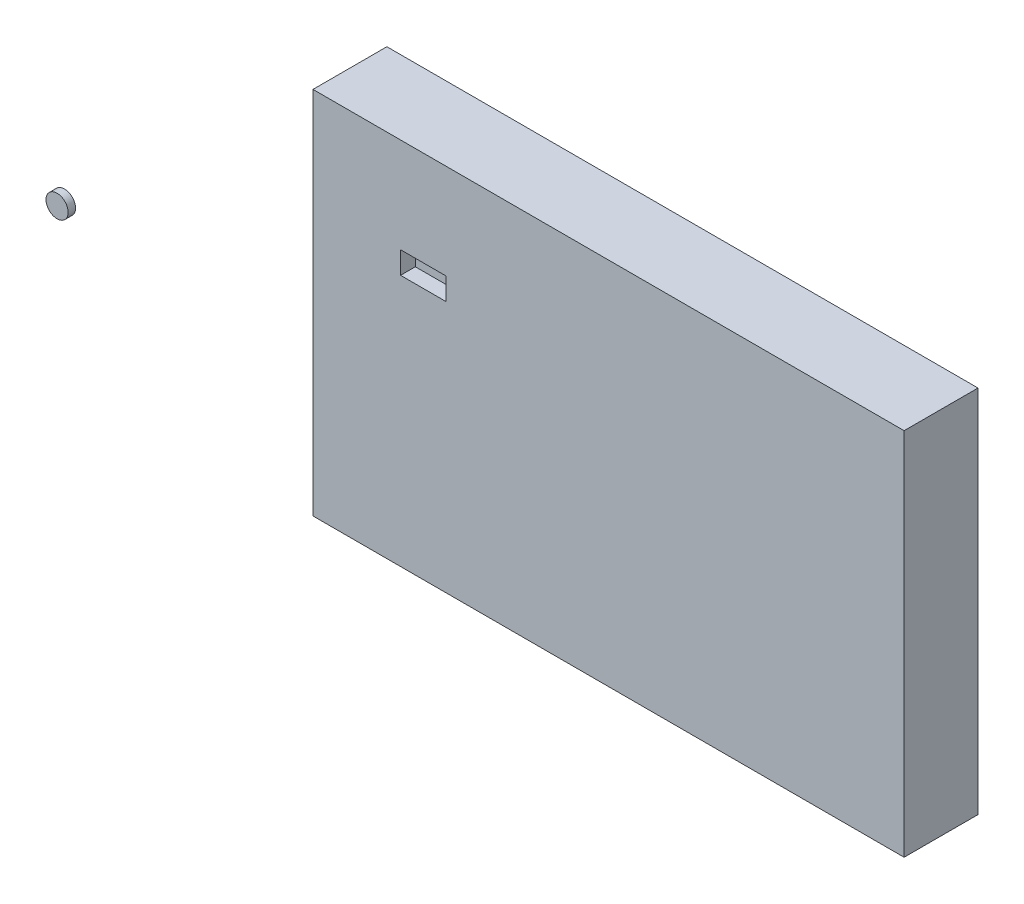
SolidWorks part; units mm, degrees
material "AISI 1020"
ref_plane "Front" through (0, 0, 0) normal (0, 0, 1) x (1, 0, 0)
ref_plane "Top" through (0, 0, 0) normal (0, 1, 0) x (1, 0, 0)
ref_plane "Right" through (0, 0, 0) normal (1, 0, 0) x (0, 0, -1)
sketch "Sketch1" plane through (0, 0, 0) normal (0, 0, 1) x (1, 0, 0)
  line L1 (0, 0) -> (80, 0)
  line L2 (0, 0) -> (0, 50)
  line L3 (0, 50) -> (80, 50)
  line L4 (80, 0) -> (80, 50)
  dimension "D1" = 80
  dimension "D2" = 50
extrude "Boss-Extrude1" add sketch "Sketch1" along normal blind 10
sketch "Sketch2" plane through (0, 0, 10) normal (0, 0, 1) x (1, 0, 0)
  line L1 (11.8518, 37.134) -> (18.0091, 37.134)
  line L2 (11.8518, 37.134) -> (11.8518, 34.134)
  line L3 (11.8518, 34.134) -> (18.0091, 34.134)
  line L4 (18.0091, 37.134) -> (18.0091, 34.134)
  dimension "D1" = 3
extrude "Cut-Extrude1" cut sketch "Sketch2" against normal blind 2
sketch "Sketch3" plane through (0, 0, 0) normal (0, 0, 1) x (1, 0, 0)
  circle A0 centre (-43.6336, 10.0141) radius 1.5
  dimension "D1" = 3
extrude "Boss-Extrude2" add sketch "Sketch3" along normal blind 1 separate body
equation "\"NumDocs\"= swApp.GetDocumentCount  'Automatic variable \"swApp\""
equation "\"UpdateStamp\"= Part.GetUpdateStamp 'Pre-loaded variable \"Part\""
equation "\"Val1\"= MsgBox(\"Currently active document: \" & swApp.ActiveDoc.GetTitle & vbCrLf & \"This message generated by: \" & Part.GetTitle) 'ActiveDoc and Part can be different"
equation "\"Val2\"= msgbox(Part.Extension.CustomPropertyManager(\"\").Get(\"MycustomProperty\"))  '\"Stringing together\" objects"
equation "\"Val3\"= 1:: Dim myStr as String:: If (Len(Part.GetMaterialPropertyName2(Part.ConfigurationManager.ActiveConfiguration.Name, myStr))<1) Then Part.Extension.RunCommand swCommands_EditMaterial,\"\" '\"::\" for multiple lines"
equation "\"Val5\"=part.extension.showsmartmessage(\"SmartMessages look like this!\",10000,true,true) 'A SmartMessage"
equation "\"Val6\"= Part.Extension.CustomPropertyManager(\"\").Set(\"DocLe\" & \"velProp\", \"Document level\") 'Setting a document-level property"
equation "\"Val7\"= Part.Extension.CustomPropertyManager(Part.ConfigurationManager.ActiveConfiguration.Name).Set(\"ConfigSpe\" & \"cProp\", \"Set for \" & Part.ConfigurationManager.ActiveConfiguration.Name & \" configuration\") 'Setting a config-specific property"
equation "\"Val9\"= Part.Extension.CustomPropertyManager(\"\").Set(\"NonExiste\" & \"ntProp\", \"This does not work\") 'Can't set a property that doesn't exist"
equation "\"Val10\"= Part.Extension.CustomPropertyManager(\"\").Delete(\"MightExi\" & \"stProp\") ::Part.Extension.CustomPropertyManager(\"\").Add2 \"MightExi\" & \"stProp\", swCustomInfoText, \"Guaranteed existence\" 'Use 2 lines to delete (if exists) then add"
equation "\"FileAgeInDays\"= Round(cDate(Part.SummaryInfo(swSumInfoSaveDate))-cDate(Part.SummaryInfo(swSumInfoCreateDate)),0) 'Manipulate file properties"
equation "\"Val11\"= IIF(True,MsgBox(\"Result is True\"), MsgBox(\"But code for False executes anyway\")) 'IIF does not actually branch"
equation "\"Val12\"= 1::Dim myPart As Variant:: For Each myPart In swApp.GetDocuments:: MsgBox myPart.GetTitle:: Next myPart' Looping is possible, but difficult"
equation "\"Val12\"= msgbox(\"d2@sketch1\"& vbcrlf & \"SW-mass\"& vbcrlf & \"AnotherCustomProperty\")             '\"Special values\" filter"
equation "\"Val13\"= \"CodePayload\" 'Code stored in custom property"
equation "\"Val14\"= \"Code1\"\"Code2\"\"Code3\"  'Concatenating code in properties"
